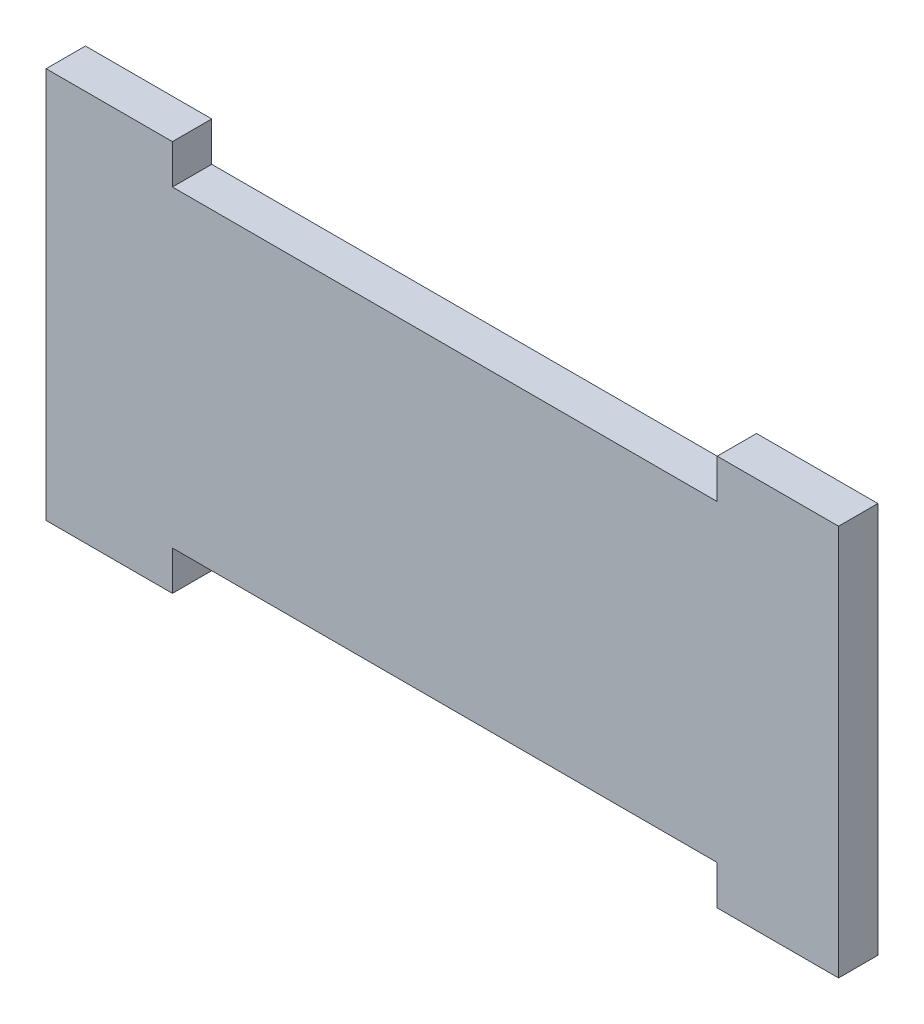
SolidWorks part; units mm, degrees
material "Acrylic (Medium-high impact)"
ref_plane "Front Plane" through (0, 0, 0) normal (0, 0, 1) x (1, 0, 0)
ref_plane "Top Plane" through (0, 0, 0) normal (0, 1, 0) x (1, 0, 0)
ref_plane "Right Plane" through (0, 0, 0) normal (1, 0, 0) x (0, 0, -1)
sketch "Sketch2" plane through (0, 0, 0) normal (0, 0, 1) x (1, 0, 0)
  line L0 (-45.9, 0) -> (-51, 0) construction
  line L1 (-51, 0) -> (-51, -1.5875) construction
  line L2 (-51, -1.5875) -> (-45.9, -1.5875) construction
  line L3 (-45.9, -1.5875) -> (-45.9, 0) construction
  line L8 (-45.9, 0) -> (-51, 0)
  line L9 (-51, 0) -> (-51, -1.5875)
  line L10 (-51, -1.5875) -> (-45.9, -1.5875)
  line L11 (-45.9, -1.5875) -> (-45.9, 0)
  line L12 (-19, 0) -> (-23.9, 0)
  line L13 (-23.9, 0) -> (-23.9, -1.5875)
  line L14 (-23.9, -1.5875) -> (-19, -1.5875)
  line L15 (-19, -1.5875) -> (-19, 0)
  line L16 (-51, -7.9) -> (-19, -7.9) construction
  line L17 (-19, -1.5875) -> (-51, -1.5875)
  line L18 (-19, -1.5875) -> (-19, -14.2125)
  line L19 (-19, -14.2125) -> (-51, -14.2125)
  line L20 (-51, -1.5875) -> (-51, -14.2125)
  line L21 (-19, -14.2125) -> (-19, -15.8)
  line L22 (-23.9, -14.2125) -> (-19, -14.2125)
  line L23 (-23.9, -15.8) -> (-23.9, -14.2125)
  line L24 (-19, -15.8) -> (-23.9, -15.8)
  line L25 (-45.9, -14.2125) -> (-45.9, -15.8)
  line L26 (-51, -14.2125) -> (-45.9, -14.2125)
  line L27 (-51, -15.8) -> (-51, -14.2125)
  line L28 (-45.9, -15.8) -> (-51, -15.8)
  line L32 (-19, 0) -> (-23.9, 0)
  line L33 (-19, -1.5875) -> (-19, 0)
  line L34 (-23.9, -1.5875) -> (-19, -1.5875)
  line L35 (-23.9, 0) -> (-23.9, -1.5875)
  line L36 (-19, 0) -> (-23.9, 0) construction
  line L37 (-19, -1.5875) -> (-19, 0) construction
  line L38 (-23.9, -1.5875) -> (-19, -1.5875) construction
  line L39 (-23.9, 0) -> (-23.9, -1.5875) construction
  dimension "D1" = 15.8
  dimension "D2" = 0
extrude "Boss-Extrude1" add sketch "Sketch2" along normal blind 1.5875 contours L16 L20 L19 L18 | L28 L25 L19 L27 | L20 L16 L18 L14 L17 L10 | L10 L11 L8 L9 | L14 L15 L12 L13 | L24 L21 L19 L23
